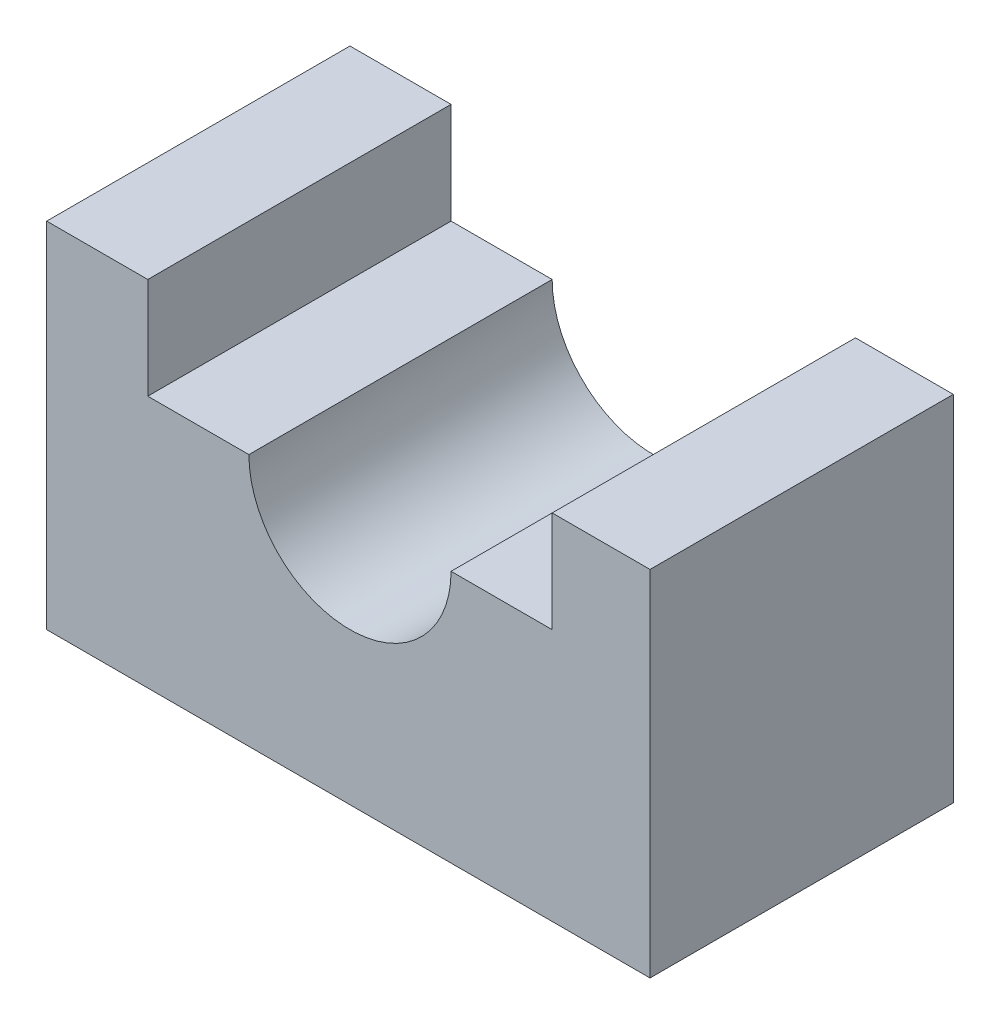
SolidWorks part; units mm, degrees
ref_plane "Front Plane" through (0, 0, 0) normal (0, 0, 1) x (1, 0, 0)
ref_plane "Top Plane" through (0, 0, 0) normal (0, 1, 0) x (1, 0, 0)
ref_plane "Right Plane" through (0, 0, 0) normal (1, 0, 0) x (0, 0, -1)
sketch "Sketch1" plane through (0, 0, 0) normal (0, 0, 1) x (1, 0, 0)
  line L0 (-30, 17.5) -> (-20, 17.5)
  line L1 (-20, 17.5) -> (-20, 7.5)
  line L2 (-30, 17.5) -> (-30, -17.5) construction
  line L3 (29.681, 16.9847) -> (29.681, -18.0153) construction
  line L4 (-20, 7.5) -> (-10, 7.5)
  line L5 (-30, -17.5) -> (29.681, -17.5)
  line L6 (-30, -17.5) -> (-30, 16.9847)
  line L8 (29.681, -17.5) -> (29.681, 16.9847)
  line L9 (29.681, 16.9847) -> (29.681, 17.5)
  line L10 (29.681, 17.5) -> (20, 17.5)
  line L11 (20, 17.5) -> (20, 7.5)
  line L12 (20, 7.5) -> (10, 7.5)
  line L13 (-30, 17.5) -> (-30, 16.9847)
  arc A0 (-10, 7.5) -> (10, 7.5) centre (0, 7.5) ccw
  point P4 (0, 0)
  point P8 (0, 0)
  point P12 (29.681, -0.5153)
  point P32 (-30, 0)
extrude "Boss-Extrude2" add sketch "Sketch1" along normal blind 30
